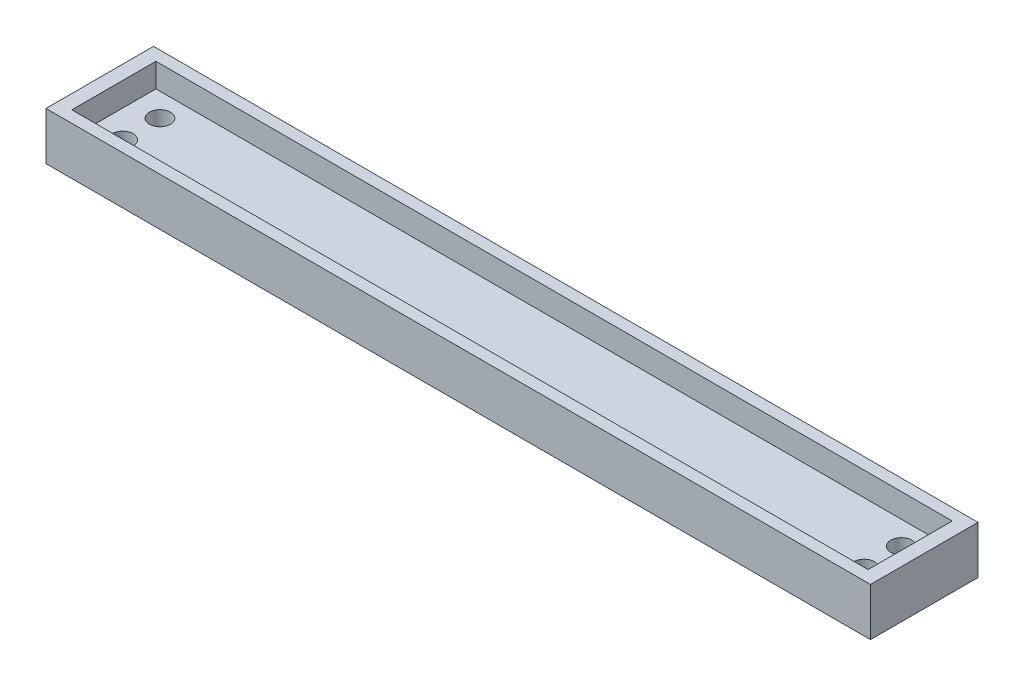
SolidWorks part; units mm, degrees
ref_plane "Front Plane" through (0, 0, 0) normal (0, 0, 1) x (1, 0, 0)
ref_plane "Top Plane" through (0, 0, 0) normal (0, 1, 0) x (1, 0, 0)
ref_plane "Right Plane" through (0, 0, 0) normal (1, 0, 0) x (0, 0, -1)
sketch "Sketch1" plane through (0, 0, 0) normal (0, 1, 0) x (1, 0, 0)
  line L1 (0, 0) -> (219.075, 0)
  line L2 (0, 0) -> (0, 28.575)
  line L3 (0, 28.575) -> (219.075, 28.575)
  line L4 (219.075, 0) -> (219.075, 28.575)
  dimension "D1" = 219.075
  dimension "D2" = 28.575
extrude "Boss-Extrude1" add sketch "Sketch1" along normal blind 12.7
sketch "Sketch2" plane through (0, 12.7, 0) normal (0, 1, 0) x (1, 0, 0)
  line L0 (0, 14.2875) -> (219.075, 14.2875) construction
  line L1 (0, 28.575) -> (0, 0) construction
  line L2 (219.075, 0) -> (219.075, 28.575) construction
  line L3 (109.5375, 28.575) -> (109.5375, 0) construction
  line L4 (219.075, 28.575) -> (0, 28.575) construction
  line L5 (0, 0) -> (219.075, 0) construction
  line L7 (3.7465, 25.4635) -> (215.3285, 25.4635)
  line L8 (3.7465, 25.4635) -> (3.7465, 3.1115)
  line L9 (3.7465, 3.1115) -> (215.3285, 3.1115)
  line L10 (215.3285, 25.4635) -> (215.3285, 3.1115)
  point P16 (109.5375, 25.4635)
  point P17 (215.3285, 14.2875)
  dimension "D1" = 211.582
  dimension "D2" = 22.352
extrude "Cut-Extrude1" cut sketch "Sketch2" against normal blind 6.35
sketch "Sketch4" plane through (0, 6.35, 0) normal (0, 1, 0) x (1, 0, 0)
  line L0 (3.7465, 14.2875) -> (215.3285, 14.2875) construction
  line L1 (3.7465, 25.4635) -> (3.7465, 3.1115) construction
  line L2 (215.3285, 3.1115) -> (215.3285, 25.4635) construction
  line L3 (109.5375, 25.4635) -> (109.5375, 3.1115) construction
  line L4 (215.3285, 25.4635) -> (3.7465, 25.4635) construction
  line L5 (3.7465, 3.1115) -> (215.3285, 3.1115) construction
  circle A0 centre (11.0363, 19.2405) radius 2.794
  circle A1 centre (11.0363, 9.3345) radius 2.794
  circle A2 centre (208.0387, 9.3345) radius 2.794
  circle A3 centre (208.0387, 19.2405) radius 2.794
  dimension "D1" = 5.588
  dimension "D2" = 98.5012
  dimension "D3" = 4.953
extrude "Cut-Extrude2" cut sketch "Sketch4" against normal through all
